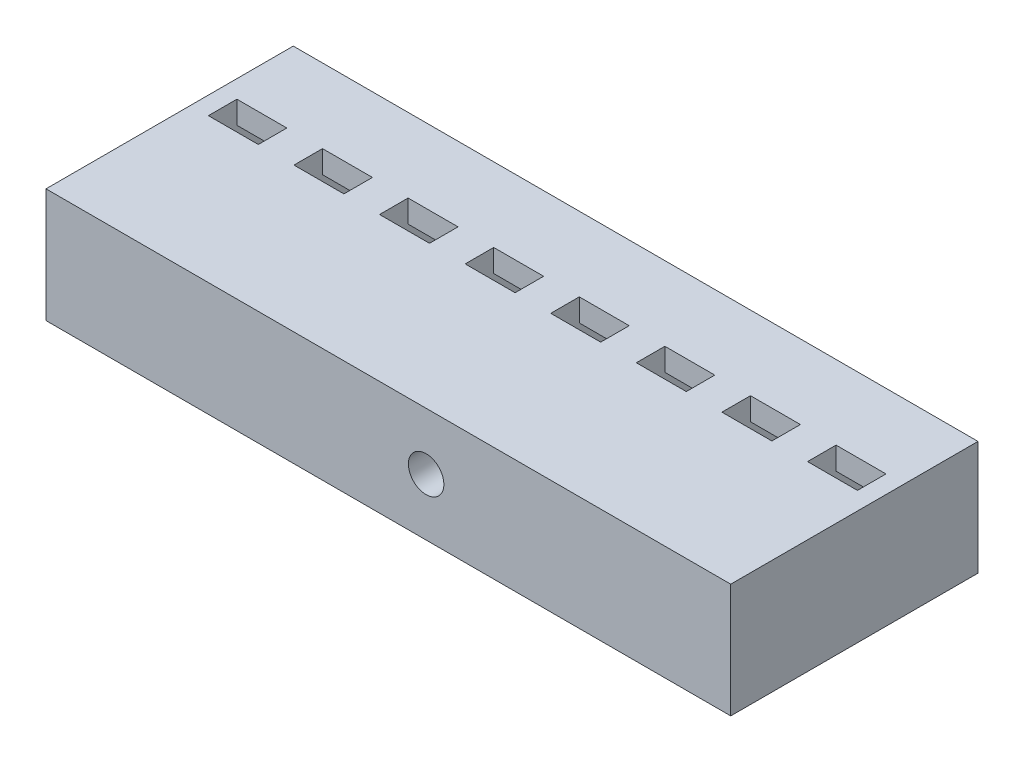
SolidWorks part; units mm, degrees
ref_plane "Front Plane" through (0, 0, 0) normal (0, 0, 1) x (1, 0, 0)
ref_plane "Top Plane" through (0, 0, 0) normal (0, 1, 0) x (1, 0, 0)
ref_plane "Right Plane" through (0, 0, 0) normal (1, 0, 0) x (0, 0, -1)
sketch "Sketch1" plane through (0, 0, 0) normal (0, 1, 0) x (1, 0, 0)
  line L1 (0, 0) -> (-72, 0)
  line L2 (0, 0) -> (0, 22)
  line L3 (0, 22) -> (-72, 22)
  line L4 (-72, 0) -> (-72, 22)
  line L5 (0, 0) -> (-72, 22) construction
  line L6 (0, 22) -> (-72, 0) construction
  point P4 (-36, 11)
  dimension "D1" = 22
  dimension "D2" = 72
extrude "Boss-Extrude1" add sketch "Sketch1" along normal blind 12
sketch "Sketch2" plane through (0, 12, 0) normal (0, 1, 0) x (1, 0, 0)
  line L0 (-72, 0) -> (-63, 0) construction
  line L2 (-72, 0) -> (0, 0) construction
  line L7 (-67.5, 0) -> (-67.5, 12.7) construction
  line L13 (-70.125, 14.2) -> (-64.875, 14.2)
  line L19 (-70.125, 14.2) -> (-70.125, 11.2)
  line L20 (-70.125, 11.2) -> (-64.875, 11.2)
  line L21 (-64.875, 14.2) -> (-64.875, 11.2)
  line L22 (-70.125, 14.2) -> (-64.875, 11.2) construction
  line L23 (-70.125, 11.2) -> (-64.875, 14.2) construction
  point P7 (-36, 23.9)
  point P23 (-73.5, 12.7)
  dimension "D1" = 9
  dimension "D2" = 5.25
  dimension "D3" = 3
extrude "Cut-Extrude1" cut sketch "Sketch2" against normal through all
pattern_linear "LPattern2" count 8 spacing 9 along (1, 0, 0) of "Cut-Extrude1"
sketch "Sketch3" plane through (0, 0, -22) normal (0, 0, -1) x (-1, 0, 0)
  line L0 (72, 6) -> (63, 6) construction
  line L2 (72, 12) -> (72, 0) construction
  line L8 (64.875, 2.375) -> (70.125, 2.375)
  line L9 (64.875, 2.375) -> (64.875, 9.625)
  line L10 (64.875, 9.625) -> (70.125, 9.625)
  line L11 (70.125, 2.375) -> (70.125, 9.625)
  line L12 (64.875, 2.375) -> (70.125, 9.625) construction
  line L13 (64.875, 9.625) -> (70.125, 2.375) construction
  point P4 (64.5, 6)
  point P5 (67.5, 6)
  dimension "D1" = 9
  dimension "D2" = 7.25
  dimension "D3" = 5.25
extrude "Cut-Extrude2" cut sketch "Sketch3" against normal through all
pattern_linear "LPattern3" count 8 spacing 9 along (1, 0, 0) of "Cut-Extrude2"
sketch "Sketch4" plane through (0, 0, 0) normal (0, 0, 1) x (1, 0, 0)
  line L1 (-72, 0) -> (0, 0)
  line L2 (-72, 0) -> (-72, 12)
  line L3 (-72, 12) -> (0, 12)
  line L4 (0, 0) -> (0, 12)
  line L5 (-72, 0) -> (0, 12) construction
  line L6 (-72, 12) -> (0, 0) construction
  point P4 (-36, 6)
extrude "Boss-Extrude2" add sketch "Sketch4" against normal blind 4
sketch "Sketch11" plane through (0, 0, 0) normal (0, 0, 1) x (1, 0, 0)
  line L1 (-72, 12) -> (0, 12)
  line L2 (-72, 12) -> (-72, 0)
  line L3 (-72, 0) -> (0, 0)
  line L4 (0, 12) -> (0, 0)
extrude "Boss-Extrude3" add sketch "Sketch11" along normal blind 4
sketch "Sketch12" plane through (0, 0, 4) normal (0, 0, 1) x (1, 0, 0)
  line L0 (0, 6) -> (-32.03, 6) construction
  line L1 (0, 0) -> (0, 12) construction
  circle A0 centre (-32.03, 6) radius 1.865
  dimension "D2" = 3.73
  dimension "D1" = 32.03
extrude "Cut-Extrude9" cut sketch "Sketch12" against normal blind 6
